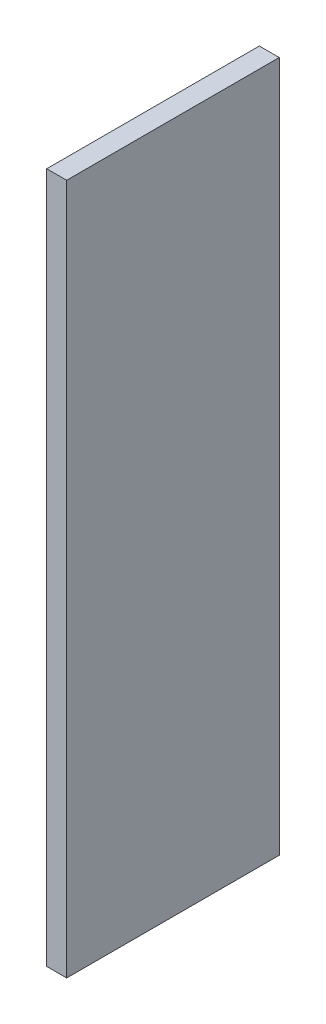
SolidWorks part; units mm, degrees
ref_plane "Front Plane" through (0, 0, 0) normal (0, 0, 1) x (1, 0, 0)
ref_plane "Top Plane" through (0, 0, 0) normal (0, 1, 0) x (1, 0, 0)
ref_plane "Right Plane" through (0, 0, 0) normal (1, 0, 0) x (0, 0, -1)
sketch "Sketch1" plane through (0, 0, 0) normal (1, 0, 0) x (0, 0, -1)
  line L1 (-30.4666, 612.4196) -> (172.7334, 612.4196)
  line L2 (-30.4666, 612.4196) -> (-30.4666, -47.9804)
  line L3 (-30.4666, -47.9804) -> (172.7334, -47.9804)
  line L4 (172.7334, 612.4196) -> (172.7334, -47.9804)
extrude "Boss-Extrude1" add sketch "Sketch1" along normal blind 19.05 contours L2 L1 L4 L3
